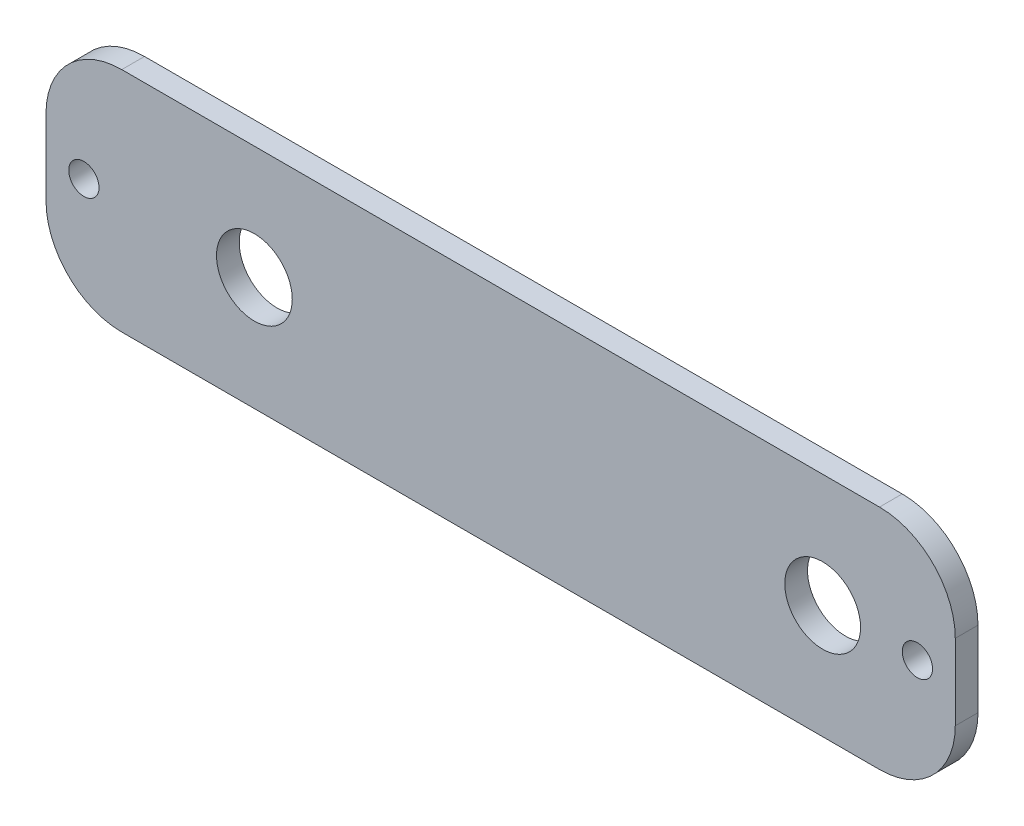
SolidWorks part; units mm, degrees
ref_plane "Plan de face" through (0, 0, 0) normal (0, 0, 1) x (1, 0, 0)
ref_plane "Plan de dessus" through (0, 0, 0) normal (0, 1, 0) x (1, 0, 0)
ref_plane "Plan de droite" through (0, 0, 0) normal (1, 0, 0) x (0, 0, -1)
sketch "Esquisse1" plane through (0, 0, 0) normal (0, 0, 1) x (1, 0, 0)
  line L1 (0, 0) -> (120, 0)
  line L2 (0, 0) -> (0, -30)
  line L3 (0, -30) -> (120, -30)
  line L4 (120, 0) -> (120, -30)
  circle A0 centre (115, -15) radius 2
  circle A1 centre (5, -15) radius 2
  point P11 (0, 0)
  dimension "D3" = 4
  dimension "D4" = 4
  dimension "D1" = 120
  dimension "D2" = 30
  dimension "D5" = 15
  dimension "D6" = 15
  dimension "D7" = 110
  dimension "D8" = 5
extrude "Boss.-Extru.1" add sketch "Esquisse1" along normal blind 3
fillet "Congé1" radius 10 4 edges at (0, -30, 1.5) (0, 0, 1.5) (120, -30, 1.5) (120, 0, 1.5)
sketch "Esquisse2" plane through (0, 0, 3) normal (0, 0, 1) x (1, 0, 0)
  line L2 (110, 0) -> (10, 0) construction
  line L3 (120, -20) -> (120, -10) construction
  circle A0 centre (27.5, -15) radius 5
  circle A1 centre (102.5, -15) radius 5
  dimension "D1" = 10
  dimension "D2" = 10
  dimension "D3" = 75
  dimension "D4" = 17.5
  dimension "D5" = 15
  dimension "D6" = 15
extrude "Enlèv. mat.-Extru.1" cut sketch "Esquisse2" against normal blind 3
